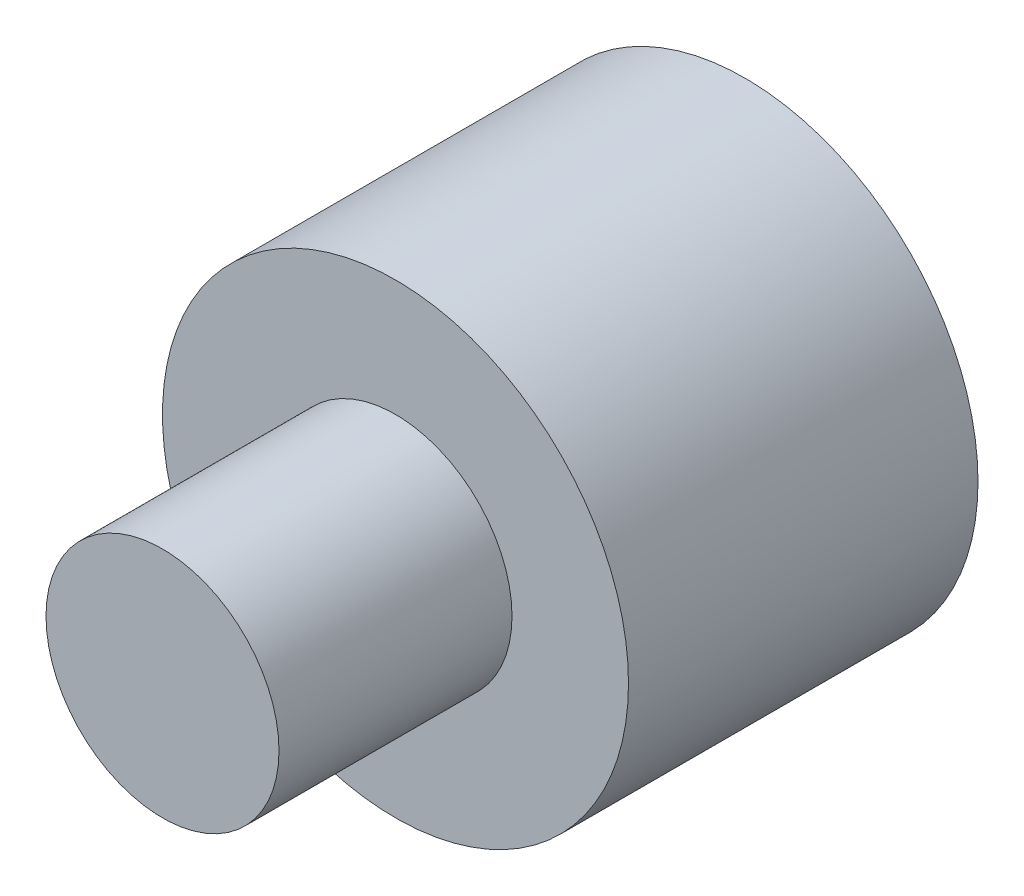
SolidWorks part; units mm, degrees
ref_plane "Front Plane" through (0, 0, 0) normal (0, 0, 1) x (1, 0, 0)
ref_plane "Top Plane" through (0, 0, 0) normal (0, 1, 0) x (1, 0, 0)
ref_plane "Right Plane" through (0, 0, 0) normal (1, 0, 0) x (0, 0, -1)
sketch "Sketch1" plane through (0, 0, 0) normal (0, 0, 1) x (1, 0, 0)
  circle A0 centre (0, 0) radius 20
extrude "Boss-Extrude1" add sketch "Sketch1" along normal blind 30
sketch "Sketch2" plane through (0, 0, 30) normal (0, 0, 1) x (1, 0, 0)
  circle A0 centre (0, 0) radius 10
extrude "Boss-Extrude2" add sketch "Sketch2" along normal blind 20 contours A0
